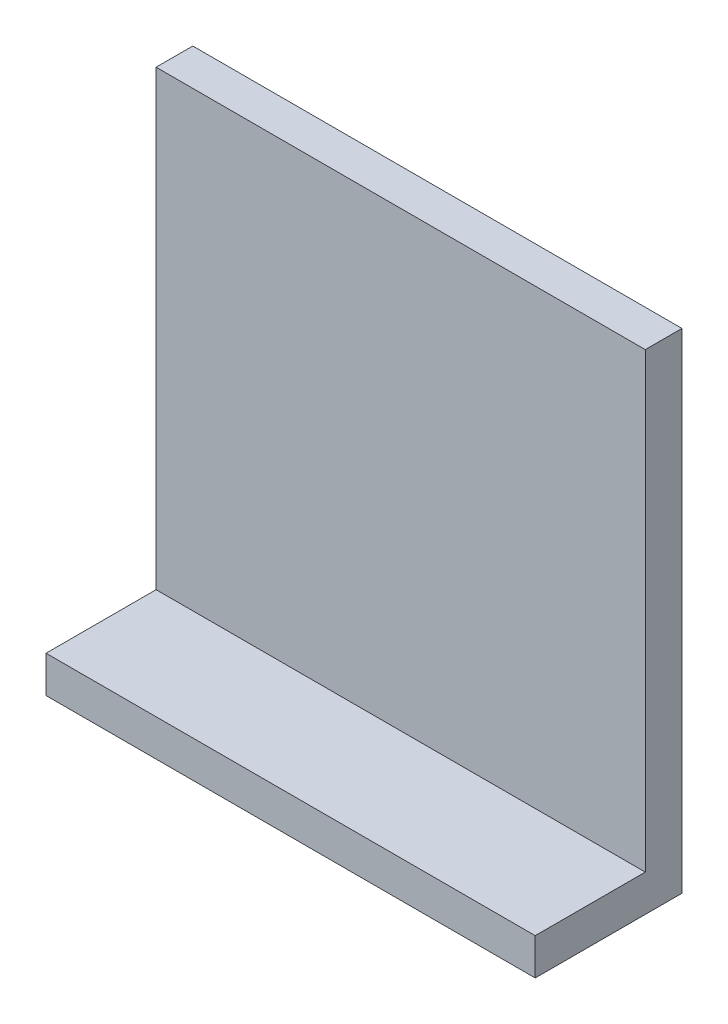
SolidWorks part; units mm, degrees
material "AISI 1035 Acero (SS)"
ref_plane "Alzado" through (0, 0, 0) normal (0, 0, 1) x (1, 0, 0)
ref_plane "Planta" through (0, 0, 0) normal (0, 1, 0) x (1, 0, 0)
ref_plane "Vista lateral" through (0, 0, 0) normal (1, 0, 0) x (0, 0, -1)
sketch "Croquis1" plane through (0, 0, 0) normal (0, 0, 1) x (1, 0, 0)
  line L1 (0, 0) -> (20, 0)
  line L2 (0, 0) -> (0, 20)
  line L3 (0, 20) -> (20, 20)
  line L4 (20, 0) -> (20, 20)
  dimension "D1" = 20
  dimension "D2" = 20
extrude "Saliente-Extruir1" add sketch "Croquis1" along normal blind 6
sketch "Croquis2" plane through (20, 0, 0) normal (1, 0, 0) x (0, 0, -1)
  line L0 (0, 0) -> (0, 20) construction
  line L1 (-6, 20) -> (-1.5, 20)
  line L2 (-6, 20) -> (-6, 1.5)
  line L3 (-6, 1.5) -> (-1.5, 1.5)
  line L4 (-1.5, 20) -> (-1.5, 1.5)
  line L5 (-6, 0) -> (0, 0) construction
  dimension "D1" = 1.5
  dimension "D2" = 1.5
extrude "Cortar-Extruir1" cut sketch "Croquis2" against normal through all
